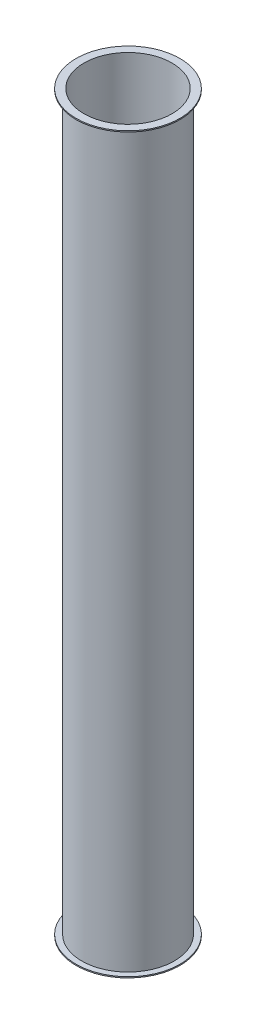
SolidWorks part; units mm, degrees
material "AISI 304"
ref_plane "Piano frontale" through (0, 0, 0) normal (0, 0, 1) x (1, 0, 0)
ref_plane "Piano superiore" through (0, 0, 0) normal (0, 1, 0) x (1, 0, 0)
ref_plane "Piano destro" through (0, 0, 0) normal (1, 0, 0) x (0, 0, -1)
sketch "Schizzo1" plane through (0, 0, 0) normal (0, 1, 0) x (1, 0, 0)
  circle A0 centre (0, 0) radius 39
extrude "Estrusione-Sottile1" add sketch "Schizzo1" along normal mid plane 650 thin
sketch "Schizzo2" plane through (0, 325, 0) normal (0, 1, 0) x (1, 0, 0)
  circle A0 centre (0, 0) radius 41 construction
  circle A1 centre (0, 0) radius 41
  circle A2 centre (0, 0) radius 46
extrude "Estrusione-Estrusione1" add sketch "Schizzo2" against normal blind 1
sketch "Schizzo3" plane through (0, -325, 0) normal (0, -1, 0) x (1, 0, 0)
  circle A0 centre (0, 0) radius 41 construction
  circle A1 centre (0, 0) radius 41
  circle A2 centre (0, 0) radius 46 construction
  circle A3 centre (0, 0) radius 46
extrude "Estrusione-Estrusione2" add sketch "Schizzo3" against normal blind 1
sketch "Schizzo4" plane through (0, -325, 0) normal (0, -1, 0) x (1, 0, 0)
  line L0 (24.5909, 0) -> (-24.5909, 0) construction
  line L1 (0, -22.0959) -> (0, 22.0959) construction
  point P5 (0, 0)
  point P9 (0, 0)
sketch "Schizzo5" plane through (0, 325, 0) normal (0, 1, 0) x (1, 0, 0)
  line L0 (24.5909, 0) -> (-24.5909, 0) construction
  line L1 (24.5909, 0) -> (-24.5909, 0) construction
  line L2 (0, 22.0959) -> (0, -22.0959) construction
  line L3 (0, 22.0959) -> (0, -22.0959) construction
